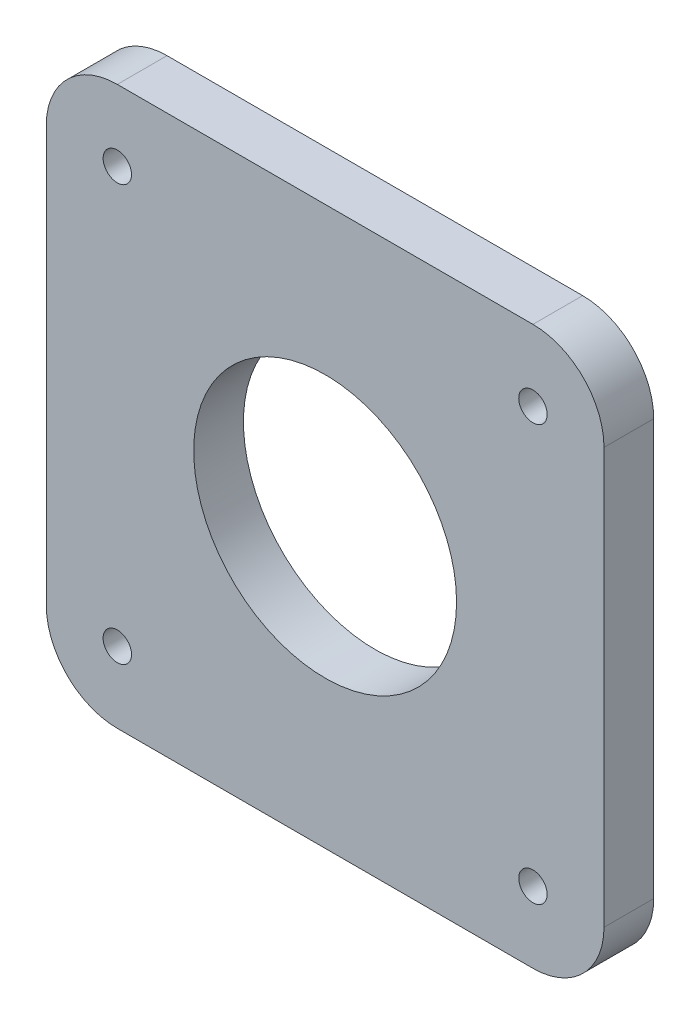
SolidWorks part; units mm, degrees
material "ABS"
ref_plane "Front Plane" through (0, 0, 0) normal (0, 0, 1) x (1, 0, 0)
ref_plane "Top Plane" through (0, 0, 0) normal (0, 1, 0) x (1, 0, 0)
ref_plane "Right Plane" through (0, 0, 0) normal (1, 0, 0) x (0, 0, -1)
sketch "Sketch1" plane through (0, 0, 0) normal (0, 0, 1) x (1, 0, 0)
  line L1 (-39.25, -39.25) -> (39.25, -39.25)
  line L2 (-39.25, -39.25) -> (-39.25, 39.25)
  line L3 (-39.25, 39.25) -> (39.25, 39.25)
  line L4 (39.25, -39.25) -> (39.25, 39.25)
  line L5 (-39.25, -39.25) -> (39.25, 39.25) construction
  line L6 (-39.25, 39.25) -> (39.25, -39.25) construction
  point P0 (0, 0)
  dimension "D1" = 78.5
extrude "Boss-Extrude1" add sketch "Sketch1" along normal mid plane 7
fillet "Fillet1" radius 10 4 edges at (-39.25, -39.25, 0) (39.25, -39.25, 0) (39.25, 39.25, 0) (-39.25, 39.25, 0)
sketch "Sketch2" plane through (0, 0, 3.5) normal (0, 0, 1) x (1, 0, 0)
  line L0 (0, 0) -> (-35355.3391, 35355.3391) construction
  line L1 (0, 0) -> (0, 50000) construction
  line L2 (0, 0) -> (-50000, 0) construction
  circle A0 centre (-29.25, 29.25) radius 2
  arc A8 (-29.25, 39.25) -> (-39.25, 29.25) centre (-29.25, 29.25) ccw construction
  circle A9 centre (-29.25, -29.25) radius 2
  circle A10 centre (29.25, 29.25) radius 2
  circle A11 centre (29.25, -29.25) radius 2
  dimension "D2" = 4
  dimension "D3" = 0
  dimension "D1" = 45
extrude "Cut-Extrude1" cut sketch "Sketch2" against normal through all
sketch "Sketch3" plane through (0, 0, 3.5) normal (0, 0, 1) x (1, 0, 0)
  circle A0 centre (0, 0) radius 18.5
  dimension "D1" = 37
extrude "Cut-Extrude2" cut sketch "Sketch3" against normal through all
